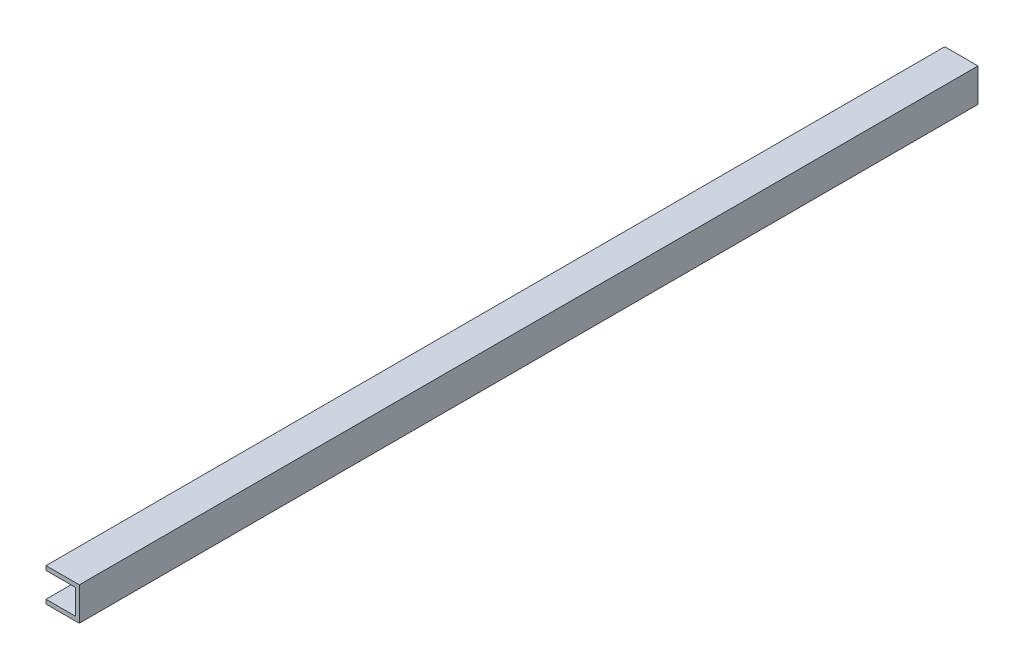
SolidWorks part; units mm, degrees
ref_plane "Front Plane" through (0, 0, 0) normal (0, 0, 1) x (1, 0, 0)
ref_plane "Top Plane" through (0, 0, 0) normal (0, 1, 0) x (1, 0, 0)
ref_plane "Right Plane" through (0, 0, 0) normal (1, 0, 0) x (0, 0, -1)
sketch "Sketch1" plane through (0, 0, 0) normal (0, 0, 1) x (1, 0, 0)
  line L0 (-8.3528, 0.4772) -> (-8.3528, -2.6978)
  line L1 (-8.3528, -2.6978) -> (13.9992, -2.6978)
  line L2 (13.9992, -2.6978) -> (13.9992, -21.7478)
  line L3 (13.9992, -21.7478) -> (-8.3528, -21.7478)
  line L4 (-8.3528, -21.7478) -> (-8.3528, -24.9228)
  line L5 (-8.3528, -24.9228) -> (17.0472, -24.9228)
  line L6 (17.0472, -24.9228) -> (17.0472, 0.4772)
  line L7 (17.0472, 0.4772) -> (-8.3528, 0.4772)
  dimension "D1" = 3.175
  dimension "D2" = 3.175
  dimension "D3" = 19.05
  dimension "D4" = 22.352
  dimension "D5" = 22.352
  dimension "D6" = 25.4
  dimension "D7" = 25.4
  dimension "D8" = 25.4
extrude "Boss-Extrude1" add sketch "Sketch1" along normal blind 685.8
